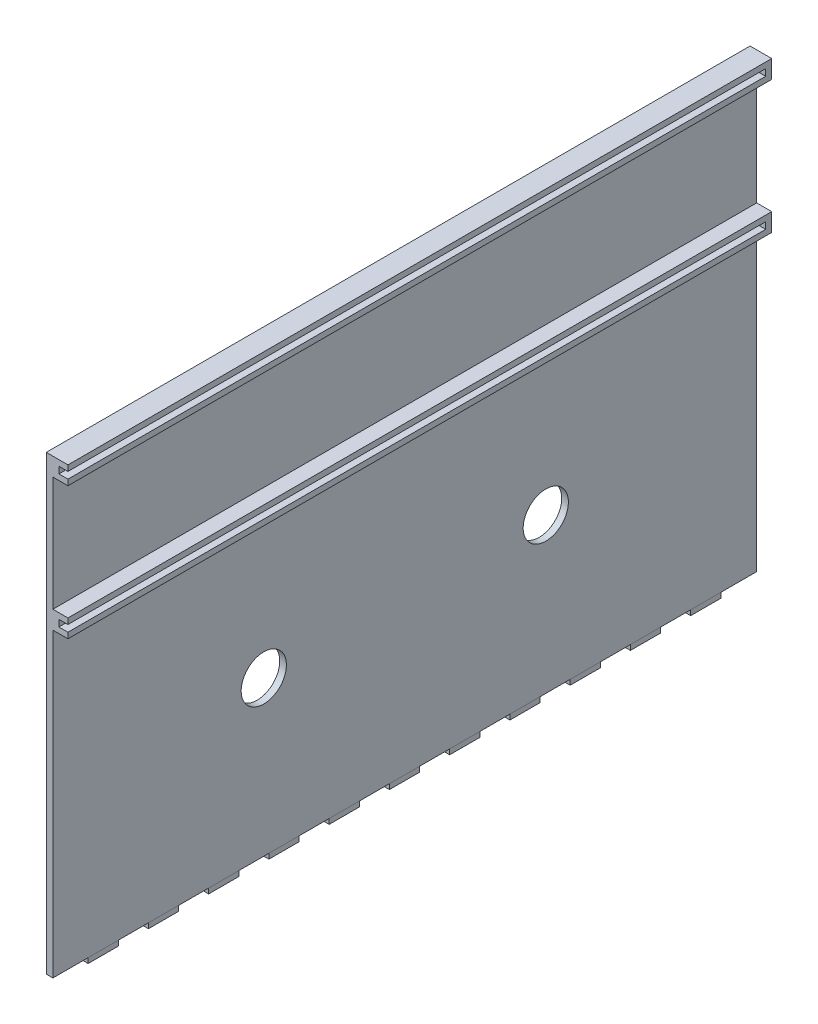
SolidWorks part; units mm, degrees
ref_plane "Front Plane" through (0, 0, 0) normal (0, 0, 1) x (1, 0, 0)
ref_plane "Top Plane" through (0, 0, 0) normal (0, 1, 0) x (1, 0, 0)
ref_plane "Right Plane" through (0, 0, 0) normal (1, 0, 0) x (0, 0, -1)
sketch "草图4" plane through (0, 0, 0) normal (1, 0, 0) x (0, 0, -1)
  line L1 (116.8, -75) -> (-116.8, -75)
  line L2 (116.8, -75) -> (116.8, 75)
  line L3 (116.8, 75) -> (-116.8, 75)
  line L4 (-116.8, -75) -> (-116.8, 75)
  line L5 (116.8, -75) -> (-116.8, 75) construction
  line L6 (116.8, 75) -> (-116.8, -75) construction
  point P0 (0, 0)
  dimension "D1" = 233.6
  dimension "D2" = 150
extrude "凸台-拉伸2" add sketch "草图4" along normal blind 2.2
sketch "草图6" plane through (0, -75, 0) normal (0, -1, 0) x (1, 0, 0)
  line L6 (2.1, 15) -> (2.1, 25)
  line L10 (2.1, 15) -> (0.1, 15)
  line L11 (2.1, -5) -> (0.1, -5)
  line L12 (2.1, -5) -> (2.1, 5)
  line L13 (2.1, 5) -> (0.1, 5)
  line L14 (0.1, -5) -> (0.1, 5)
  line L15 (2.1, -5) -> (0.1, 5) construction
  line L16 (2.1, 5) -> (0.1, -5) construction
  line L17 (0.1, 15) -> (0.1, 25)
  line L18 (2.1, 25) -> (0.1, 25)
  line L19 (2.1, 35) -> (2.1, 45)
  line L20 (2.1, 35) -> (0.1, 35)
  line L21 (0.1, 35) -> (0.1, 45)
  line L22 (2.1, 45) -> (0.1, 45)
  line L23 (2.1, 55) -> (2.1, 65)
  line L24 (2.1, 55) -> (0.1, 55)
  line L25 (0.1, 55) -> (0.1, 65)
  line L26 (2.1, 65) -> (0.1, 65)
  line L27 (2.1, 75) -> (2.1, 85)
  line L28 (2.1, 75) -> (0.1, 75)
  line L29 (0.1, 75) -> (0.1, 85)
  line L30 (2.1, 85) -> (0.1, 85)
  line L31 (2.1, 95) -> (2.1, 105)
  line L32 (2.1, 95) -> (0.1, 95)
  line L33 (0.1, 95) -> (0.1, 105)
  line L34 (2.1, 105) -> (0.1, 105)
  line L35 (2.1, -25) -> (2.1, -15)
  line L36 (2.1, -25) -> (0.1, -25)
  line L37 (0.1, -25) -> (0.1, -15)
  line L38 (2.1, -15) -> (0.1, -15)
  line L39 (2.1, -45) -> (2.1, -35)
  line L40 (2.1, -45) -> (0.1, -45)
  line L41 (0.1, -45) -> (0.1, -35)
  line L42 (2.1, -35) -> (0.1, -35)
  line L43 (2.1, -65) -> (2.1, -55)
  line L44 (2.1, -65) -> (0.1, -65)
  line L45 (0.1, -65) -> (0.1, -55)
  line L46 (2.1, -55) -> (0.1, -55)
  line L47 (2.1, -85) -> (2.1, -75)
  line L48 (2.1, -85) -> (0.1, -85)
  line L49 (0.1, -85) -> (0.1, -75)
  line L50 (2.1, -75) -> (0.1, -75)
  line L51 (2.1, -105) -> (2.1, -95)
  line L52 (2.1, -105) -> (0.1, -105)
  line L53 (0.1, -105) -> (0.1, -95)
  line L54 (2.1, -95) -> (0.1, -95)
  point P6 (1.1, 0)
  dimension "D1" = 2
  dimension "D2" = 10
  dimension "D3" = 6
extrude "凸台-拉伸3" add sketch "草图6" along normal blind 1.8
sketch "草图7" plane through (2.2, 0, 0) normal (1, 0, 0) x (0, 0, -1)
  line L0 (116.8, 25) -> (-116.8, 25)
  line L5 (-116.8, -75) -> (116.8, -75) construction
  line L6 (116.8, -75) -> (116.8, 75) construction
  line L9 (-116.8, 75) -> (-116.8, -75) construction
  line L14 (-116.8, 31) -> (-116.8, 25)
  line L15 (116.8, 31) -> (116.8, 25)
  line L16 (-116.8, 31) -> (116.8, 31)
  line L17 (116.8, 69) -> (116.8, 75)
  line L18 (-116.8, 69) -> (116.8, 69)
  line L19 (-116.8, 69) -> (-116.8, 75)
  line L20 (116.8, 75) -> (-116.8, 75)
  dimension "D1" = 100
  dimension "D2" = 6
extrude "凸台-拉伸4" add sketch "草图7" along normal blind 5
sketch "草图8" plane through (7.2, 0, 0) normal (1, 0, 0) x (0, 0, -1)
  line L0 (0, 31) -> (0, 25)
  line L1 (116.8, 31) -> (-116.8, 31) construction
  line L2 (-116.8, 25) -> (116.8, 25) construction
  line L3 (-116.8, 31) -> (-116.8, 25) construction
  line L4 (114.8, 29.1) -> (114.8, 26.9)
  line L5 (116.8, 26.9) -> (-116.8, 26.9)
  line L7 (116.8, 29.1) -> (-116.8, 29.1)
  line L8 (-116.8, 26.9) -> (-116.8, 29.1)
  line L9 (116.8, 26.9) -> (-116.8, 29.1) construction
  line L10 (116.8, 29.1) -> (-116.8, 26.9) construction
  line L12 (114.8, 70.9) -> (114.8, 73.1)
  line L18 (-116.8, 73.1) -> (-116.8, 70.9)
  line L19 (116.8, 73.1) -> (-116.8, 73.1)
  line L20 (116.8, 70.9) -> (-116.8, 70.9)
  point P6 (0, 28)
  line M7 (-116.8, 31) -> (-116.8, 25)
  dimension "D1" = 2.2
extrude "切除-拉伸1" cut sketch "草图8" against normal blind 3 contours L4 L7 L0 L5 | L0 L7 L5 M7 | L20 L12 L19 L18
sketch "Sketch1" plane through (2.2, 0, 0) normal (1, 0, 0) x (0, 0, -1)
  line L0 (-116.8, 25) -> (-116.8, -75) construction
  line L1 (116.8, -75) -> (116.8, 25) construction
  circle A0 centre (-46.8, -23.7453) radius 7.5
  circle A1 centre (46.8, -23.7453) radius 7.5
  dimension "D1" = 15
  dimension "D2" = 15
  dimension "D4" = 70
  dimension "D5" = 70
extrude "Cut-Extrude1" cut sketch "Sketch1" against normal blind 10
